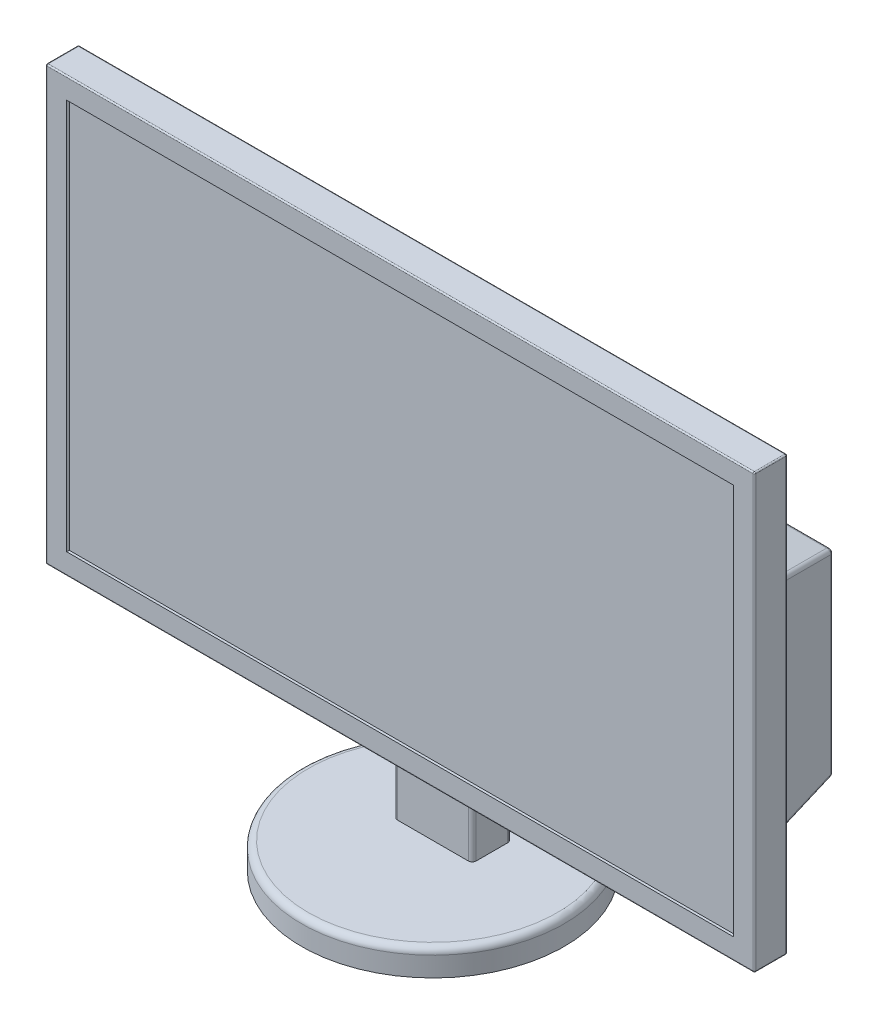
SolidWorks part; units mm, degrees
ref_plane "Front Plane" through (0, 0, 0) normal (0, 0, 1) x (1, 0, 0)
ref_plane "Top Plane" through (0, 0, 0) normal (0, 1, 0) x (1, 0, 0)
ref_plane "Right Plane" through (0, 0, 0) normal (1, 0, 0) x (0, 0, -1)
sketch "Sketch1" plane through (0, 0, 0) normal (0, 0, 1) x (1, 0, 0)
  line L1 (-270, -165) -> (270, -165)
  line L2 (-270, -165) -> (-270, 165)
  line L3 (-270, 165) -> (270, 165)
  line L4 (270, -165) -> (270, 165)
  line L5 (-270, -165) -> (270, 165) construction
  line L6 (-270, 165) -> (270, -165) construction
  point P0 (0, 0)
  dimension "D1" = 540
  dimension "D2" = 330
extrude "Boss-Extrude1" add sketch "Sketch1" against normal blind 25
sketch "Sketch2" plane through (0, 0, -25) normal (0, 0, -1) x (-1, 0, 0)
  line L0 (-270, -165) -> (-270, 165) construction
  line L1 (-250, -85) -> (250, -85)
  line L2 (-250, -85) -> (-250, 65)
  line L3 (-250, 65) -> (250, 65)
  line L4 (250, -85) -> (250, 65)
  line L5 (-250, -85) -> (250, 65) construction
  line L6 (-250, 65) -> (250, -85) construction
  line L7 (270, 165) -> (270, -165) construction
  line L8 (270, -165) -> (-270, -165) construction
  line L9 (-270, 165) -> (270, 165) construction
  point P0 (0, -10)
  dimension "D1" = 20
  dimension "D2" = 20
  dimension "D3" = 80
  dimension "D4" = 100
extrude "Boss-Extrude2" add sketch "Sketch2" along normal blind 55
draft "Draft1" type of draft neutral plane draft angle 1 faces to draft 4 face at (0, -85, -52.5) face at (-250, -10, -52.5) face at (0, 65, -52.5) face at (250, -10, -52.5) neutral plane through (0, 0, -80) neutral plane normal (0, 0, -1) parameters "D1"=1
draft "Draft2" type of draft neutral plane draft angle 10 faces to draft 4 face at (0, 65.48, -52.5) face at (-250.48, -10, -52.5) face at (0, -85.48, -52.5) face at (250.48, -10, -52.5) neutral plane through (0, 0, -80) neutral plane normal (0, 0, -1) parameters "D1"=10
draft "Draft3" type of draft neutral plane draft angle 20 faces to draft 4 parameters "D1"=20
draft "Draft4" type of draft neutral plane draft angle 10 faces to draft 4 face at (260, -10, -52.5252) face at (0, 78.3395, -43.3502) face at (0, -98.3395, -43.3502) face at (-260, -10, -52.5252) neutral plane through (0, 0, -80) neutral plane normal (0, 0, -1) parameters "D1"=10
sketch "Sketch4" plane through (0, 0, -25) normal (0, 0, -1) x (-1, 0, 0)
  line L0 (-250, -85) -> (250, -85) construction
  line L1 (-30, -245) -> (30, -245)
  line L2 (-30, -245) -> (-30, -85)
  line L3 (-30, -85) -> (30, -85)
  line L4 (30, -245) -> (30, -85)
  line L5 (270, -165) -> (-270, -165) construction
  dimension "D1" = 80
  dimension "D2" = 60
  dimension "D3" = 30
extrude "Boss-Extrude3" add sketch "Sketch4" along normal blind 30
sketch "Sketch5" plane through (0, -245, 0) normal (0, -1, 0) x (-1, 0, 0)
  line L0 (-30, 25) -> (30, 25) construction
  circle A0 centre (0, 25) radius 100
  dimension "D1" = 200
extrude "Boss-Extrude4" add sketch "Sketch5" against normal blind 20
fillet "Fillet1" radius 3 4 edges at (30, -157.2041, -55) (30, -195, -25) (-30, -157.2041, -55) (-30, -195, -25)
fillet "Fillet2" radius 1 13 edges at (0, 165, -25) (0, 165, 0) (270, 165, -12.5) (270, 0, -25) (270, 0, 0) (270, -165, -12.5) (150, -165, -25) (-150, -165, -25) (0, -165, 0) (-270, -165, -12.5) (-270, 0, -25) (-270, 0, 0) (-270, 165, -12.5)
fillet "Fillet3" radius 3 8 edges at (250, -10, -80) (0, 65, -80) (-250, -10, -80) (0, -85, -80) (-254.849, -89.849, -52.5) (-254.849, 69.849, -52.5) (254.849, 69.849, -52.5) (254.849, -89.849, -52.5)
fillet "Fillet4" radius 5 1 edges at (0, -225, -125)
sketch "Sketch6" plane through (0, 0, 0) normal (0, 0, 1) x (1, 0, 0)
  line L0 (-269, 164) -> (-269, -164) construction
  line L1 (-254, -149) -> (254, -149)
  line L2 (-254, -149) -> (-254, 149)
  line L3 (-254, 149) -> (254, 149)
  line L4 (254, -149) -> (254, 149)
  line L5 (269, 164) -> (-269, 164) construction
  line L6 (269, -164) -> (269, 164) construction
  line L7 (-269, -164) -> (269, -164) construction
  dimension "D1" = 15
  dimension "D2" = 15
  dimension "D3" = 15
  dimension "D4" = 15
extrude "Cut-Extrude1" cut sketch "Sketch6" against normal blind 2
